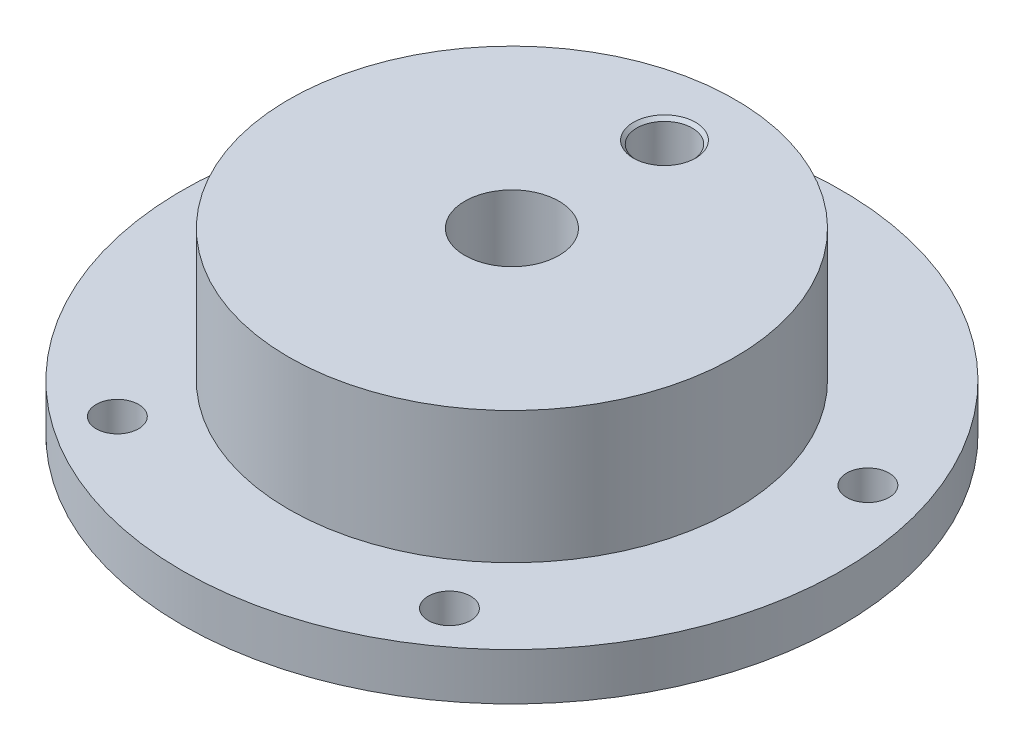
SolidWorks part; units mm, degrees
material "1023 Carbon Steel Sheet (SS)"
ref_plane "Front Plane" through (0, 0, 0) normal (0, 0, 1) x (1, 0, 0)
ref_plane "Top Plane" through (0, 0, 0) normal (0, 1, 0) x (1, 0, 0)
ref_plane "Right Plane" through (0, 0, 0) normal (1, 0, 0) x (0, 0, -1)
sketch "Sketch1" plane through (0, 0, 0) normal (0, 0, 1) x (1, 0, 0)
  line L0 (0, 0) -> (-10, 0) construction
  line L1 (-10, 0) -> (-10, -38)
  line L2 (-10, -38) -> (-12.5, -38)
  line L3 (-12.5, -38) -> (-12.5, -36.2)
  line L4 (-12.7, -36) -> (-15.542, -36)
  line L5 (-15.75, -36.208) -> (-15.75, -38)
  line L6 (-15.75, -38) -> (-18.5, -38)
  line L7 (-18.5, -38) -> (-18.5, -36.208)
  line L8 (-18.708, -36) -> (-21.542, -36)
  line L9 (-21.75, -36.208) -> (-21.75, -38)
  line L10 (-21.75, -38) -> (-24, -38)
  line L11 (-24, -38) -> (-24, -10)
  line L13 (-39.4, -10) -> (-39.4, -38)
  line L14 (-39.4, -38) -> (-42, -38)
  line L15 (-42, -38) -> (-42, -36.208)
  line L16 (-42.208, -36) -> (-45.042, -36)
  line L17 (-45.25, -36.208) -> (-45.25, -38)
  line L18 (-45.25, -38) -> (-47.75, -38)
  line L19 (-47.75, -38) -> (-47.75, -36.208)
  line L20 (-47.958, -36) -> (-50.792, -36)
  line L21 (-51, -36.208) -> (-51, -38)
  line L22 (-51, -38) -> (-70, -38)
  line L23 (-70, -38) -> (-70, -28)
  line L24 (-70, -28) -> (-47.4, -28)
  line L25 (-47.4, -28) -> (-47.4, 0)
  line L26 (-47.4, 0) -> (-10, 0)
  line L28 (-39.4, -10) -> (-24, -10)
  line L29 (0, 0) -> (0, -83.2336) construction
  arc A0 (-12.5, -36.2) -> (-12.7, -36) centre (-12.7, -36.2) ccw
  arc A1 (-15.542, -36) -> (-15.75, -36.208) centre (-15.542, -36.208) ccw
  arc A2 (-21.542, -36) -> (-21.75, -36.208) centre (-21.542, -36.208) ccw
  arc A3 (-18.5, -36.208) -> (-18.708, -36) centre (-18.708, -36.208) ccw
  arc A4 (-50.792, -36) -> (-51, -36.208) centre (-50.792, -36.208) ccw
  arc A5 (-47.75, -36.208) -> (-47.958, -36) centre (-47.958, -36.208) ccw
  arc A6 (-45.042, -36) -> (-45.25, -36.208) centre (-45.042, -36.208) ccw
  arc A7 (-42, -36.208) -> (-42.208, -36) centre (-42.208, -36.208) ccw
  point P30 (-12.5, -36)
  point P33 (-15.75, -36)
  point P36 (-21.75, -36)
  point P39 (-18.5, -36)
  point P42 (-51, -36)
  point P45 (-47.75, -36)
  point P48 (-45.25, -36)
  point P51 (-42, -36)
  dimension "D26" = 0.2
  dimension "D27" = 0.208
  dimension "D28" = 0.208
  dimension "D29" = 0.208
  dimension "D1" = 10
  dimension "D2" = 38
  dimension "D3" = 2.5
  dimension "D4" = 2
  dimension "D5" = 3.25
  dimension "D6" = 2
  dimension "D7" = 2.75
  dimension "D8" = 2
  dimension "D9" = 3.25
  dimension "D10" = 2
  dimension "D11" = 2.25
  dimension "D12" = 28
  dimension "D13" = 15.4
  dimension "D14" = 28
  dimension "D15" = 28
  dimension "D16" = 22.6
  dimension "D17" = 10
  dimension "D18" = 2.6
  dimension "D19" = 2
  dimension "D20" = 3.25
  dimension "D21" = 2.5
  dimension "D22" = 2
  dimension "D23" = 2
  dimension "D24" = 3.25
  dimension "D25" = 37.4
revolve "Revolve1" add sketch "Sketch1" angle 360 about L29
sketch "Sketch2" plane through (0, 0, 0) normal (0, 1, 0) x (1, 0, 0)
  point P0 (0, 32.4)
  dimension "D1" = 32.4
hole_wizard "G1/4 Tapped Hole1" positions "Sketch3" profile "Sketch4" tap size "G1/4" standard "BSI" end condition up to next
sketch "Sketch3" plane through (0, 0, 0) normal (0, 1, 0) x (1, 0, 0)
  point P0 (0, 32.4)
sketch "Sketch4" plane through (0, 0, -32.4) normal (1, 0, 0) x (0, 0, 1)
  line L0 (0, 0) -> (0, 10)
  line L1 (0, 10) -> (5.9, 10)
  line L2 (5.9, 10) -> (5.9, 0.7035)
  line L3 (5.9, 0.7035) -> (6.6035, 0)
  line L5 (6.6035, 0) -> (0, 0)
  line L6 (-5.9, 0.7035) -> (-6.6035, 0) construction
  line L11 (0, -6.35) -> (0, 107.95) construction
  dimension "Thru Tap Drill Dia." = 11.8
  dimension "Thru Tap Drill Depth" = 10
  dimension "Near C'Sink Dia." = 13.207
  dimension "Near C'Sink Angle" = 90
cosmetic thread "Hole Thread1" parameters "D2"=13.157
sketch "Sketch5" plane through (0, -28, 0) normal (0, 1, 0) x (1, 0, 0)
  circle A0 centre (0, 60) radius 4.5
  point P0 (0, 60)
  dimension "D1" = 60
extrude "Cut-Extrude1" cut sketch "Sketch5" against normal blind 10
sketch "Sketch6" plane through (0, 0, 0) normal (0, 0, 1) x (1, 0, 0)
  line L0 (0, -22.7338) -> (0, 22.818) construction
pattern_circular "CirPattern1" count 5 over 360 about axis through (0, 0, 0) along (0, 1, 0) of "Cut-Extrude1"
